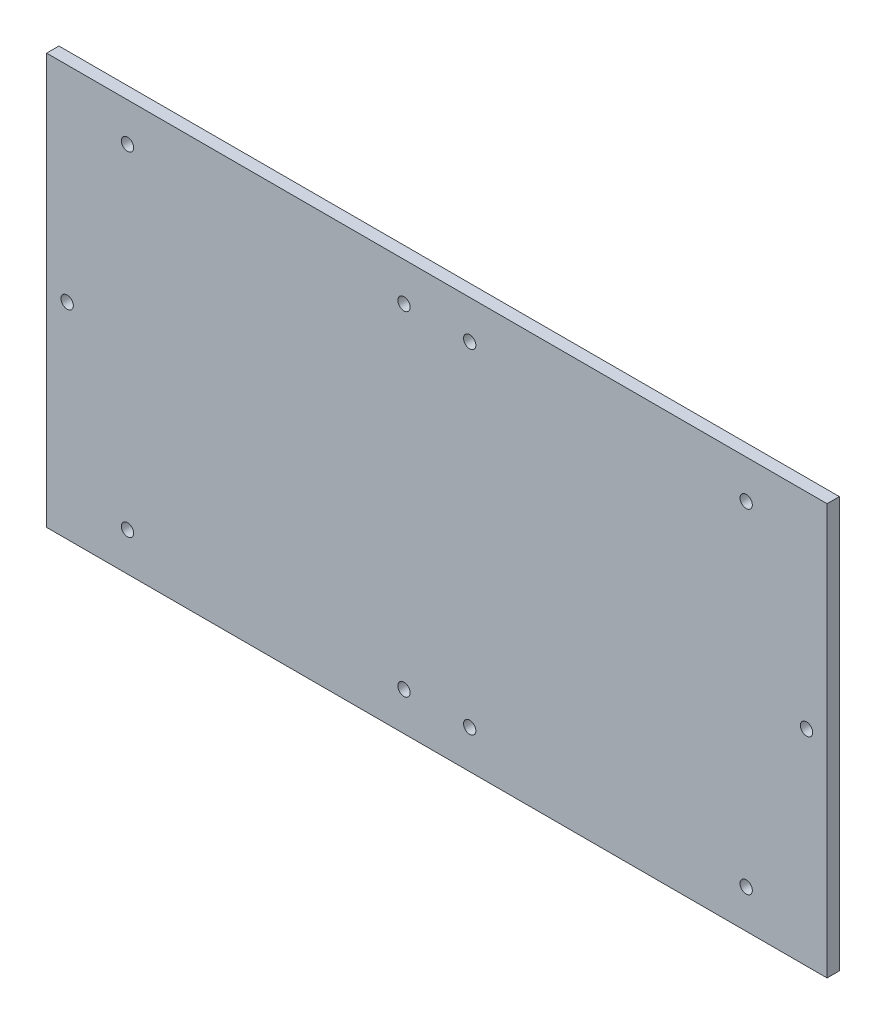
SolidWorks part; units mm, degrees
ref_plane "Front Plane" through (0, 0, 0) normal (0, 0, 1) x (1, 0, 0)
ref_plane "Top Plane" through (0, 0, 0) normal (0, 1, 0) x (1, 0, 0)
ref_plane "Right Plane" through (0, 0, 0) normal (1, 0, 0) x (0, 0, -1)
sketch "Sketch1" plane through (0, 0, 0) normal (0, 0, 1) x (1, 0, 0)
  line L1 (-95, 50) -> (95, 50)
  line L2 (-95, 50) -> (-95, -50)
  line L3 (-95, -50) -> (95, -50)
  line L4 (95, 50) -> (95, -50)
  line L5 (-95, 50) -> (95, -50) construction
  line L6 (-95, -50) -> (95, 50) construction
  point P0 (0, 0)
  dimension "D1" = 190
  dimension "D2" = 100
extrude "Boss-Extrude1" add sketch "Sketch1" along normal blind 3
sketch "Sketch2" plane through (0, 0, 3) normal (0, 0, 1) x (1, 0, 0)
  line L0 (0, 0) -> (90, 0) construction
  line L5 (75.31, 40.64) -> (75.31, -40.64) construction
  line L6 (-75.31, 40.64) -> (-8, 40.64) construction
  line L7 (75.31, -40.64) -> (8, 40.64) construction
  line L19 (-75.31, -40.64) -> (-8, -40.64) construction
  line L20 (8, 40.64) -> (8, -40.64) construction
  line L21 (0, 0) -> (0, -40.64) construction
  line L22 (8, 40.64) -> (75.31, 40.64) construction
  line L23 (8, -40.64) -> (75.31, -40.64) construction
  line L24 (-75.31, 40.64) -> (-75.31, 0) construction
  line L25 (8, -40.64) -> (75.31, 40.64) construction
  line L26 (-75.31, 0) -> (-75.31, -40.64) construction
  line L27 (-75.31, 40.64) -> (-8, -40.64) construction
  line L28 (-8, -40.64) -> (-8, 40.64) construction
  line L29 (-8, 40.64) -> (-75.31, -40.64) construction
  line L31 (0, 0) -> (-90, 0) construction
  circle A0 centre (-75.31, 40.64) radius 1.5
  circle A1 centre (-75.31, -40.64) radius 1.5
  circle A41 centre (-8, 40.64) radius 1.5
  circle A42 centre (-8, -40.64) radius 1.5
  circle A44 centre (8, 40.64) radius 1.5
  circle A45 centre (75.31, 40.64) radius 1.5
  circle A46 centre (75.31, -40.64) radius 1.5
  circle A47 centre (8, -40.64) radius 1.5
  circle A48 centre (-90, 0) radius 1.5
  circle A49 centre (90, 0) radius 1.5
  dimension "D3" = 3
  dimension "D4" = 3
  dimension "D5" = 90
  dimension "D6" = 3
  dimension "D9" = 67.31
  dimension "D10" = 3
  dimension "D11" = 3
  dimension "D8" = 67.31
  dimension "D12" = 3
  dimension "D13" = 3
  dimension "D16" = 3
  dimension "D14" = 3
  dimension "D15" = 3
  dimension "D2" = 90
  dimension "D7" = 67.31
  dimension "D18" = 40.64
  dimension "D19" = 40.64
extrude "Cut-Extrude1" cut sketch "Sketch2" against normal blind 4
